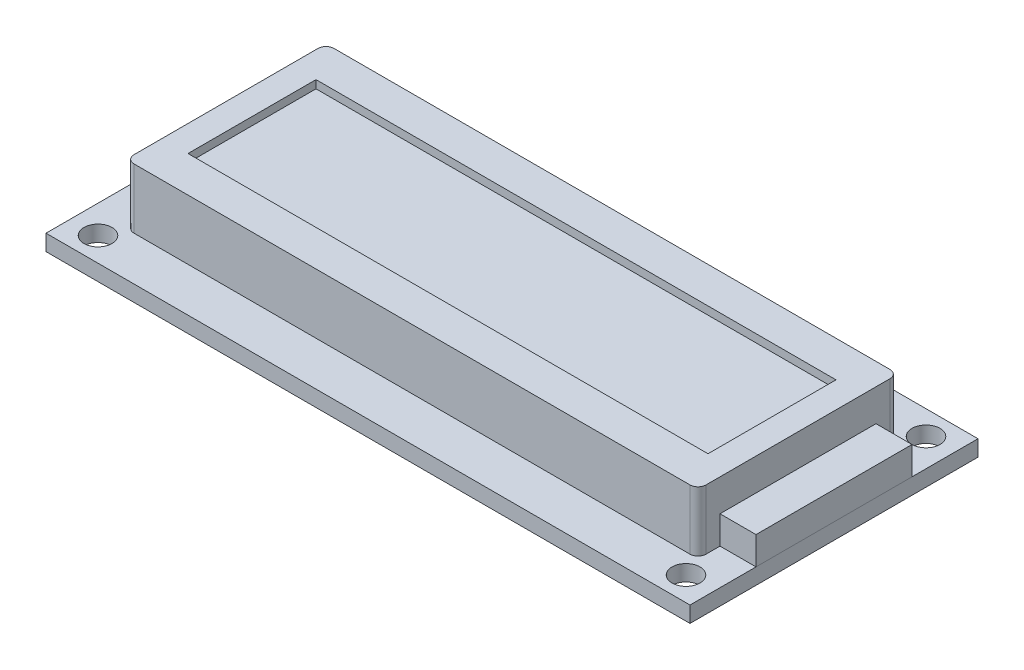
SolidWorks part; units mm, degrees
ref_plane "Front Plane" through (0, 0, 0) normal (0, 0, 1) x (1, 0, 0)
ref_plane "Top Plane" through (0, 0, 0) normal (0, 1, 0) x (1, 0, 0)
ref_plane "Right Plane" through (0, 0, 0) normal (1, 0, 0) x (0, 0, -1)
sketch "Sketch1" plane through (0, 0, 0) normal (0, 1, 0) x (1, 0, 0)
  line L1 (-43.4885, 25.4454) -> (37.0115, 25.4454)
  line L2 (-43.4885, 25.4454) -> (-43.4885, -10.5546)
  line L3 (-43.4885, -10.5546) -> (37.0115, -10.5546)
  line L4 (37.0115, 25.4454) -> (37.0115, -10.5546)
  dimension "D1" = 80.5
  dimension "D2" = 36
extrude "Boss-Extrude1" add sketch "Sketch1" along normal blind 2
sketch "Sketch2" plane through (0, 2, 0) normal (0, 1, 0) x (1, 0, 0)
  line L2 (-43.4885, 22.4454) -> (-39.9885, 22.4454) construction
  line L3 (-43.4885, 25.4454) -> (-43.4885, -10.5546) construction
  circle A0 centre (-39.9885, 22.4454) radius 1.75
  circle A1 centre (33.5115, 22.4454) radius 1.75
  circle A2 centre (33.5115, -7.5546) radius 1.75
  circle A3 centre (-39.9885, -7.5546) radius 1.75
extrude "Cut-Extrude1" cut sketch "Sketch2" against normal blind 2
sketch "Sketch3" plane through (0, 2, 0) normal (0, 1, 0) x (1, 0, 0)
  line L7 (32.5115, -5.0546) -> (-38.9885, -5.0546)
  line L8 (32.5115, -5.0546) -> (32.5115, 19.9454)
  line L9 (32.5115, 19.9454) -> (-38.9885, 19.9454)
  line L10 (-38.9885, -5.0546) -> (-38.9885, 19.9454)
  point P12 (-3.2385, 7.4454)
extrude "Boss-Extrude2" add sketch "Sketch3" along normal blind 7.5
sketch "Sketch4" plane through (0, 9.5, 0) normal (0, 1, 0) x (1, 0, 0)
  line L7 (29.2615, -0.5546) -> (-35.7385, -0.5546)
  line L8 (29.2615, -0.5546) -> (29.2615, 15.4454)
  line L9 (29.2615, 15.4454) -> (-35.7385, 15.4454)
  line L10 (-35.7385, -0.5546) -> (-35.7385, 15.4454)
  point P12 (-3.2385, 7.4454)
extrude "Cut-Extrude2" cut sketch "Sketch4" against normal blind 1
fillet "Fillet1" radius 1 4 edges at (32.5115, 5.75, 5.0546) (32.5115, 5.75, -19.9454) (-38.9885, 5.75, 5.0546) (-38.9885, 5.75, -19.9454)
sketch "Sketch5" plane through (0, 2, 0) normal (0, 1, 0) x (1, 0, 0)
  line L1 (37.0115, -10.5546) -> (37.0115, 25.4454) construction
  line L3 (32.2186, -4.7617) -> (37.0115, -4.7617) construction
  line L7 (37.0115, -2.3046) -> (32.5115, -2.3046)
  line L8 (37.0115, -2.3046) -> (37.0115, 17.1954)
  line L9 (37.0115, 17.1954) -> (32.5115, 17.1954)
  line L10 (32.5115, -2.3046) -> (32.5115, 17.1954)
  arc A1 (31.5115, -5.0546) -> (32.5115, -4.0546) centre (31.5115, -4.0546) ccw construction
  point P18 (34.7615, 7.4454)
extrude "Boss-Extrude3" add sketch "Sketch5" along normal blind 3.5
sketch "Sketch6" plane through (37.0115, 0, 0) normal (1, 0, 0) x (0, 0, -1)
  line L1 (17.1954, 5.5) -> (-2.3046, 5.5)
  line L2 (17.1954, 5.5) -> (17.1954, 2)
  line L3 (17.1954, 2) -> (-2.3046, 2)
  line L4 (-2.3046, 5.5) -> (-2.3046, 2)
extrude "Boss-Extrude4" add sketch "Sketch6" along normal blind 0.001
sketch "Sketch7" plane through (0, 0, 0) normal (0, -1, 0) x (-1, 0, 0)
  circle A0 centre (34.9885, 22.4454) radius 0.3125
  circle A1 centre (32.4885, 22.4454) radius 0.3125
  circle A2 centre (29.9885, 22.4454) radius 0.3125
  circle A3 centre (27.4885, 22.4454) radius 0.3125
  circle A4 centre (24.9885, 22.4454) radius 0.3125
  circle A5 centre (22.4885, 22.4454) radius 0.3125
  circle A6 centre (19.9885, 22.4454) radius 0.3125
  circle A7 centre (17.4885, 22.4454) radius 0.3125
  circle A8 centre (14.9885, 22.4454) radius 0.3125
  circle A9 centre (12.4885, 22.4454) radius 0.3125
  circle A10 centre (9.9885, 22.4454) radius 0.3125
  circle A11 centre (7.4885, 22.4454) radius 0.3125
  circle A12 centre (4.9885, 22.4454) radius 0.3125
  circle A13 centre (2.4885, 22.4454) radius 0.3125
  circle A14 centre (-0.0115, 22.4454) radius 0.3125
  circle A15 centre (-2.5115, 22.4454) radius 0.3125
extrude "Boss-Extrude5" add sketch "Sketch7" along normal blind 4 and the other way blind 2.5
